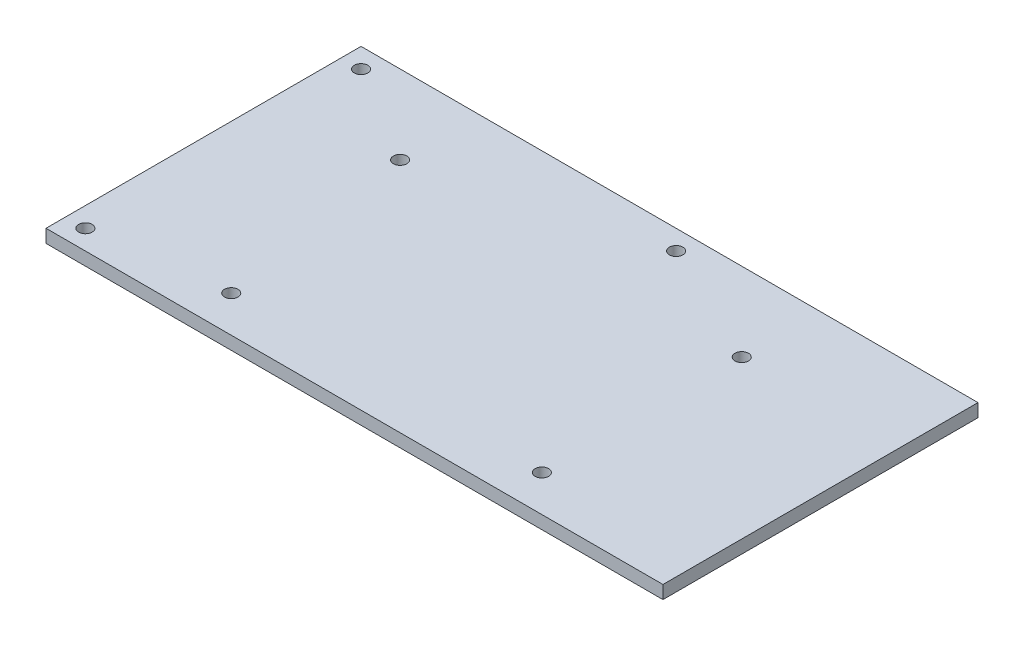
SolidWorks part; units mm, degrees
material "ABS"
ref_plane "Front Plane" through (0, 0, 0) normal (0, 0, 1) x (1, 0, 0)
ref_plane "Top Plane" through (0, 0, 0) normal (0, 1, 0) x (1, 0, 0)
ref_plane "Right Plane" through (0, 0, 0) normal (1, 0, 0) x (0, 0, -1)
sketch "Base Sketch" plane through (0, 0, 0) normal (0, 1, 0) x (1, 0, 0)
  line L1 (-74.6125, -38.1) -> (74.6125, -38.1)
  line L2 (-74.6125, -38.1) -> (-74.6125, 38.1)
  line L3 (-74.6125, 38.1) -> (74.6125, 38.1)
  line L4 (74.6125, -38.1) -> (74.6125, 38.1)
  line L5 (-74.6125, -38.1) -> (74.6125, 38.1) construction
  line L6 (-74.6125, 38.1) -> (74.6125, -38.1) construction
  point P0 (0, 0)
  dimension "D1" = 149.225
  dimension "D2" = 76.2
extrude "Base Plate" add sketch "Base Sketch" along normal blind 3.175
sketch "4-40 Hole Pattern Sketch (Guide Rail)" plane through (0, 3.175, 0) normal (0, 1, 0) x (1, 0, 0)
  line L0 (74.6125, 38.1) -> (-74.6125, 38.1) construction
  line L1 (-74.6125, 38.1) -> (-74.6125, -38.1) construction
  line L2 (-74.6125, -38.1) -> (74.6125, -38.1) construction
  circle A0 centre (-69.85, 33.3375) radius 1.6319
  circle A1 centre (-69.85, -33.3375) radius 1.6319
  circle A2 centre (6.35, 33.3375) radius 1.6319
  point P0 (-69.85, 33.3375)
  point P5 (6.35, 33.3375)
  point P6 (-69.85, -33.3375)
  dimension "D7" = 3.2639
  dimension "D8" = 3.2639
  dimension "D9" = 3.2639
  dimension "D1" = 4.7625
  dimension "D2" = 4.7625
  dimension "D3" = 4.7625
  dimension "D4" = 80.9625
  dimension "D5" = 4.7625
  dimension "D6" = 4.7625
sketch "4-40 Hole Pattern Sketch (Arduino Holes)" plane through (0, 3.175, 0) normal (0, 1, 0) x (1, 0, 0)
  line L0 (74.6125, -38.1) -> (74.6125, 38.1) construction
  line L1 (74.6125, 38.1) -> (-74.6125, 38.1) construction
  circle A0 centre (-46.1137, 19.05) radius 1.6319
  circle A1 centre (-38.6207, -29.2862) radius 1.6319
  circle A2 centre (36.5125, 19.05) radius 1.6319
  circle A3 centre (36.5125, -29.2862) radius 1.6319
  point P0 (36.5125, 19.05)
  point P5 (36.5125, -29.2862)
  point P6 (-46.1137, 19.05)
  point P7 (-38.6207, -29.2862)
  dimension "D9" = 3.2639
  dimension "D10" = 3.2639
  dimension "D11" = 3.2639
  dimension "D12" = 3.2639
  dimension "D1" = 38.1
  dimension "D2" = 19.05
  dimension "D3" = 38.1
  dimension "D4" = 48.3362
  dimension "D5" = 82.6262
  dimension "D6" = 19.05
  dimension "D7" = 48.3362
  dimension "D8" = 75.1332
extrude "4-40 Guide Rail Holes" cut sketch "4-40 Hole Pattern Sketch (Guide Rail)" against normal up to next
extrude "4-40 Arduino Holes" cut sketch "4-40 Hole Pattern Sketch (Arduino Holes)" against normal up to next
